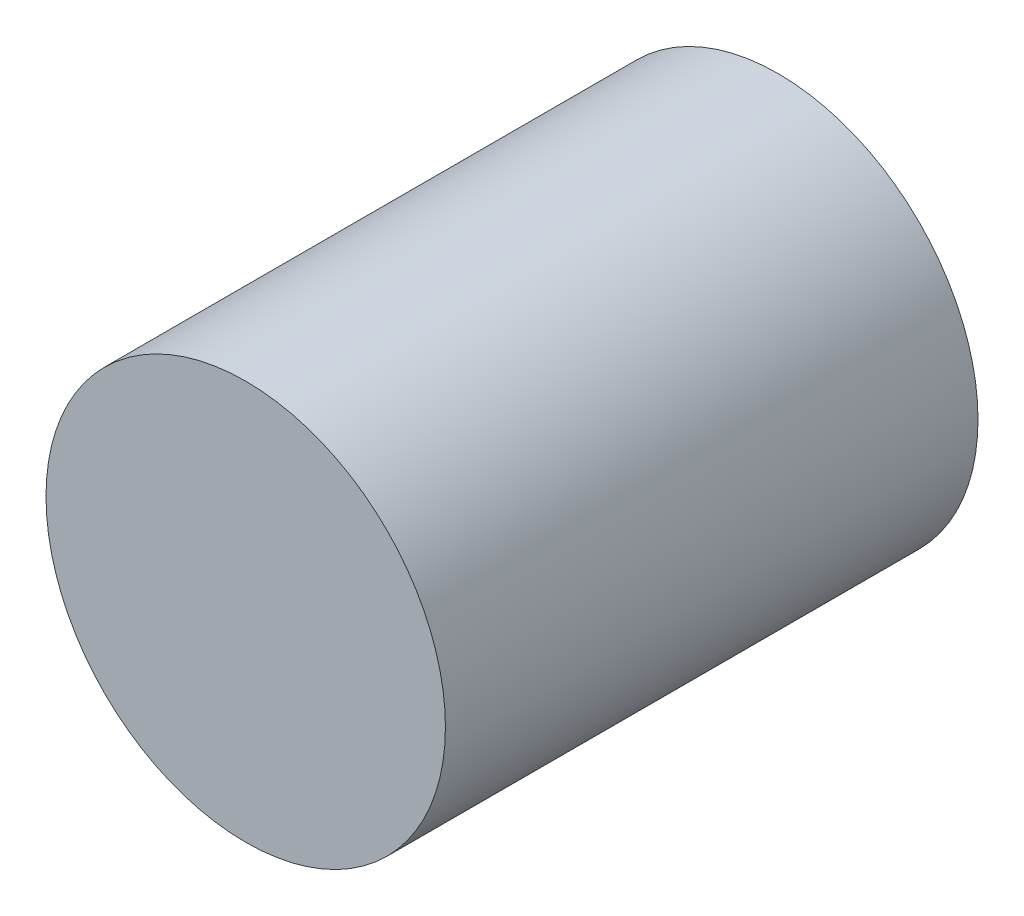
SolidWorks part; units mm, degrees
ref_plane "Front Plane" through (0, 0, 0) normal (0, 0, 1) x (1, 0, 0)
ref_plane "Top Plane" through (0, 0, 0) normal (0, 1, 0) x (1, 0, 0)
ref_plane "Right Plane" through (0, 0, 0) normal (1, 0, 0) x (0, 0, -1)
sketch "Sketch3" plane through (0, 0, 0) normal (0, 0, 1) x (1, 0, 0)
  circle A0 centre (0, 0) radius 0.75
  dimension "D1" = 1.5
extrude "Boss-Extrude1" add sketch "Sketch3" along normal blind 2
